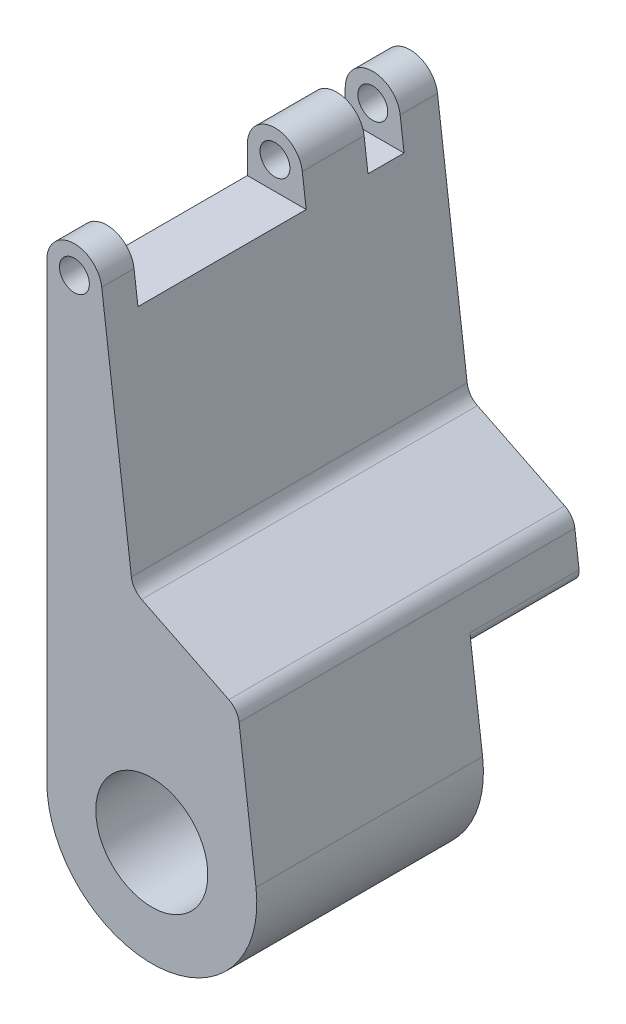
SolidWorks part; units mm, degrees
ref_plane "Front Plane" through (0, 0, 0) normal (0, 0, 1) x (1, 0, 0)
ref_plane "Top Plane" through (0, 0, 0) normal (0, 1, 0) x (1, 0, 0)
ref_plane "Right Plane" through (0, 0, 0) normal (1, 0, 0) x (0, 0, -1)
sketch "Sketch1" plane through (0, 0, 0) normal (0, 0, 1) x (1, 0, 0)
  line L0 (-7.1385, 30.7537) -> (-7.1385, 0)
  line L1 (-1.3886, 14.9418) -> (-3.4046, 30.9873)
  line L2 (-0.692, 13.962) -> (5.2357, 11.0269)
  line L3 (5.9323, 10.0471) -> (7.0828, 0.8899)
  arc A0 (-7.1385, 0) -> (7.0828, 0.8899) centre (0, 0) ccw
  arc A1 (-1.3886, 14.9418) -> (-0.692, 13.962) centre (-0.1285, 15.1001) ccw
  arc A2 (-7.1385, 30.7537) -> (-3.4046, 30.9873) centre (-5.2642, 30.7537) cw
  arc A3 (5.2357, 11.0269) -> (5.9323, 10.0471) centre (4.6722, 9.8888) cw
  dimension "D1" = 1.27
  dimension "D2" = 1.8743
  dimension "D4" = 7.1385
  dimension "D3" = 30.7537
extrude "Extrude1" add sketch "Sketch1" along normal blind 15.4071
sketch "Sketch2" plane through (0, 0, 0) normal (0, 0, -1) x (-1, 0, 0)
  line L0 (1.3886, 14.9418) -> (3.4046, 30.9873) construction
  line L1 (7.1385, 30.7537) -> (7.1385, 0) construction
  line L2 (1.3886, 14.9418) -> (3.4046, 30.9873)
  line L3 (7.1385, 30.7537) -> (7.1385, 8.4678)
  line L4 (5.5757, 6.9049) -> (-5.4735, 6.9049)
  line L5 (-7.0828, 0.8899) -> (-5.9323, 10.0471) construction
  line L6 (-5.2357, 11.0269) -> (0.692, 13.962) construction
  line L7 (-6.2207, 7.7519) -> (-5.9323, 10.0471)
  line L8 (-5.2357, 11.0269) -> (0.692, 13.962)
  arc A0 (-5.2357, 11.0269) -> (-5.9323, 10.0471) centre (-4.6722, 9.8888) ccw construction
  arc A1 (7.1385, 30.7537) -> (3.4046, 30.9873) centre (5.2642, 30.7537) ccw construction
  arc A2 (0.692, 13.962) -> (1.3886, 14.9418) centre (0.1285, 15.1001) ccw
  arc A3 (7.1385, 30.7537) -> (3.4046, 30.9873) centre (5.2642, 30.7537) ccw
  arc A4 (-5.2357, 11.0269) -> (-5.9323, 10.0471) centre (-4.6722, 9.8888) ccw
  arc A5 (-5.4735, 6.9049) -> (-6.2207, 7.7519) centre (-5.4735, 7.658) cw
  arc A6 (5.5757, 6.9049) -> (7.1385, 8.4678) centre (5.5757, 8.4678) ccw
  arc A7 (0.692, 13.962) -> (1.3886, 14.9418) centre (0.1285, 15.1001) ccw construction
  point P20 (-6.3271, 6.9049)
extrude "Extrude2" add sketch "Sketch2" along normal blind 7.4229
sketch "Sketch3" plane through (0, 0, 0) normal (0, 0, -1) x (-1, 0, 0)
  circle A0 centre (0, 0) radius 3.81
  dimension "D1" = 7.62
extrude "Extrude3" cut sketch "Sketch3" against normal through all
sketch "Sketch4" plane through (0, 0, -7.4229) normal (0, 0, -1) x (-1, 0, 0)
  circle A0 centre (5.2642, 30.7537) radius 1.016
  dimension "D1" = 2.032
extrude "Extrude4" cut sketch "Sketch4" against normal through all
sketch "Sketch6" plane through (-7.1385, 0, 0) normal (-1, 0, 0) x (0, 0, 1)
  line L1 (-4.8829, 32.6279) -> (-2.431, 32.6279)
  line L2 (-4.8829, 32.6279) -> (-4.8829, 28.8794)
  line L3 (-4.8829, 28.8794) -> (-2.431, 28.8794)
  line L4 (-2.431, 32.6279) -> (-2.431, 28.8794)
  line L5 (15.4071, 30.7537) -> (-7.4229, 30.7537) construction
  line L6 (1.7709, 32.6279) -> (13.2093, 32.6279)
  line L7 (1.7709, 32.6279) -> (1.7709, 28.8794)
  line L8 (1.7709, 28.8794) -> (13.2093, 28.8794)
  line L9 (13.2093, 32.6279) -> (13.2093, 28.8794)
  line L10 (-6.0347, 30.7537) -> (16.8859, 30.7537) construction
  line L11 (15.4071, 32.6279) -> (-7.4229, 32.6279) construction
extrude "Extrude6" cut sketch "Sketch6" against normal through all
